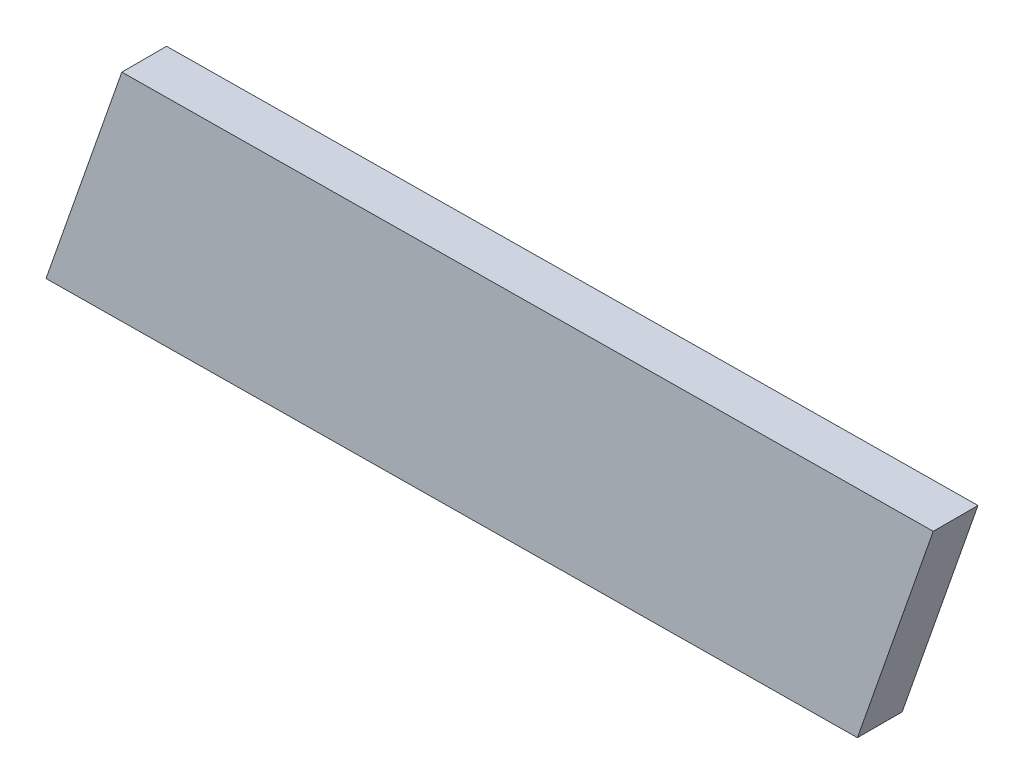
SolidWorks part; units mm, degrees
ref_plane "Front Plane" through (0, 0, 0) normal (0, 0, 1) x (1, 0, 0)
ref_plane "Top Plane" through (0, 0, 0) normal (0, 1, 0) x (1, 0, 0)
ref_plane "Right Plane" through (0, 0, 0) normal (1, 0, 0) x (0, 0, -1)
sketch "Sketch2" plane through (0, 0, 0) normal (0, 0, 1) x (1, 0, 0)
  line L0 (0, 0) -> (16.9445, 48.4219)
  line L1 (0, 0) -> (181.3329, 1.7972)
  line L2 (16.9445, 48.4219) -> (198.2774, 50.2191)
  line L3 (181.3329, 1.7972) -> (198.2774, 50.2191)
extrude "Boss-Extrude2" add sketch "Sketch2" along normal blind 10
sketch "Sketch3" plane through (0, 0, 0) normal (0, 0, -1) x (-1, 0, 0)
  line L1 (-175.0197, 23.2638) -> (-145.4876, 23.2638)
  line L2 (-175.0197, 23.2638) -> (-175.0197, 28.596)
  line L3 (-175.0197, 28.596) -> (-145.4876, 28.596)
  line L4 (-145.4876, 23.2638) -> (-145.4876, 28.596)
  line L5 (-128.6708, 23.4689) -> (-98.9336, 23.4689)
  line L6 (-128.6708, 23.4689) -> (-128.6708, 28.8011)
  line L7 (-128.6708, 28.8011) -> (-98.9336, 28.8011)
  line L8 (-98.9336, 23.4689) -> (-98.9336, 28.8011)
  line L9 (-82.9371, 23.2638) -> (-51.9694, 23.2638)
  line L10 (-82.9371, 23.2638) -> (-82.9371, 28.596)
  line L11 (-82.9371, 28.596) -> (-51.9694, 28.596)
  line L12 (-51.9694, 23.2638) -> (-51.9694, 28.596)
  line L13 (-42.9457, 23.4689) -> (-16.0797, 23.4689)
  line L14 (-42.9457, 23.4689) -> (-42.9457, 28.8011)
  line L15 (-42.9457, 28.8011) -> (-16.0797, 28.8011)
  line L16 (-16.0797, 23.4689) -> (-16.0797, 28.8011)
extrude "Boss-Extrude3" add sketch "Sketch3" along normal blind 0.5
scale "Scale1" scale about centroid uniform scaling yes scale factor 5
